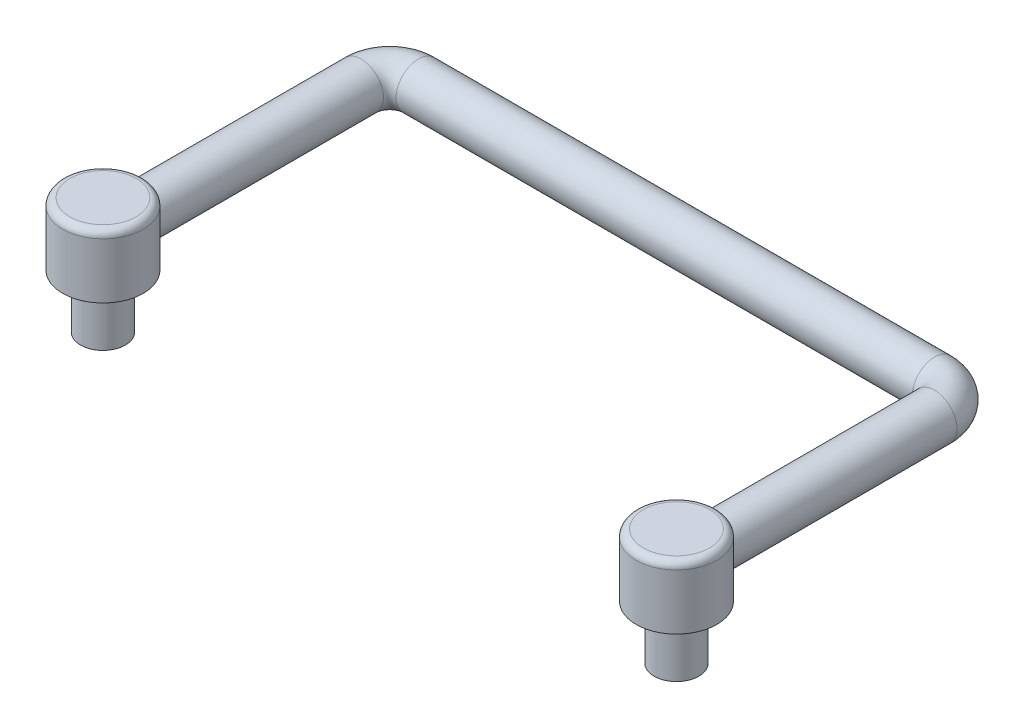
SolidWorks part; units mm, degrees
ref_plane "Front Plane" through (0, 0, 0) normal (0, 0, 1) x (1, 0, 0)
ref_plane "Top Plane" through (0, 0, 0) normal (0, 1, 0) x (1, 0, 0)
ref_plane "Right Plane" through (0, 0, 0) normal (1, 0, 0) x (0, 0, -1)
sketch "Sketch1" plane through (0, 0, 0) normal (0, 1, 0) x (1, 0, 0)
  line L0 (0, 0) -> (0, 45.72)
  line L1 (5.08, 50.8) -> (96.52, 50.8)
  line L2 (101.6, 45.72) -> (101.6, 0)
  arc A0 (5.08, 50.8) -> (0, 45.72) centre (5.08, 45.72) ccw
  arc A1 (101.6, 45.72) -> (96.52, 50.8) centre (96.52, 45.72) ccw
  dimension "D1" = 5.08
  dimension "D2" = 5.08
  dimension "D3" = 50.8
  dimension "D4" = 50.8
  dimension "D5" = 101.6
sketch "Sketch2" plane through (0, 0, 0) normal (0, 0, 1) x (1, 0, 0)
  circle A0 centre (0, 0) radius 3.9688
  dimension "D1" = 7.9375
sweep "Sweep1" add profiles "Sketch2" path "Sketch1"
sketch "Sketch3" plane through (0, 0, 0) normal (0, 1, 0) x (1, 0, 0)
  line L0 (97.6313, 0) -> (105.5687, 0) construction
  circle A0 centre (0, 0) radius 7.1438
  circle A1 centre (101.6, 0) radius 7.1438
  dimension "D1" = 14.2875
  dimension "D2" = 14.2875
extrude "Extrude1" add sketch "Sketch3" along normal mid plane 11.1125
sketch "Sketch4" plane through (0, -5.5562, 0) normal (0, -1, 0) x (1, 0, 0)
  circle A0 centre (0, 0) radius 3.9688
  circle A1 centre (101.6, 0) radius 3.9687
  dimension "D1" = 7.9375
  dimension "D2" = 7.9375
extrude "Extrude2" add sketch "Sketch4" along normal blind 9.525
fillet "Fillet1" radius 1.27 2 edges at (101.6, 5.5562, 7.1438) (0, 5.5562, 7.1438)
